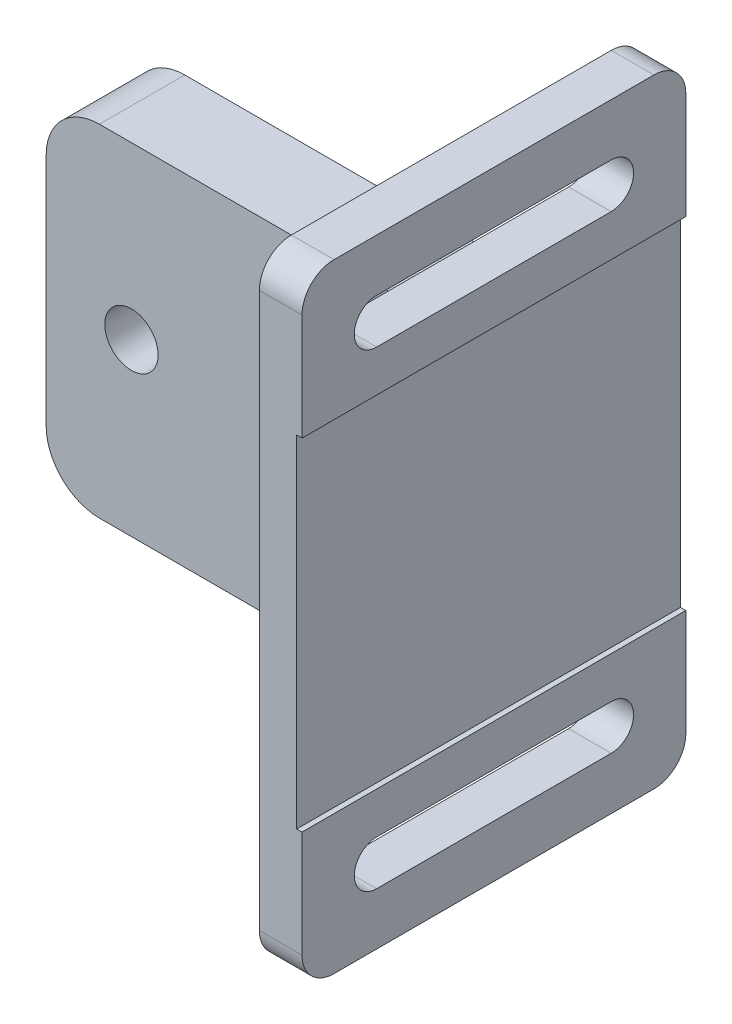
SolidWorks part; units mm, degrees
material "6061 合金"
ref_plane "前视基准面" through (0, 0, 0) normal (0, 0, 1) x (1, 0, 0)
ref_plane "上视基准面" through (0, 0, 0) normal (0, 1, 0) x (1, 0, 0)
ref_plane "右视基准面" through (0, 0, 0) normal (1, 0, 0) x (0, 0, -1)
sketch "草图1" plane through (0, 0, 0) normal (0, 0, 1) x (1, 0, 0)
  line L1 (0, 0) -> (40, 0)
  line L2 (0, 0) -> (0, 58)
  line L3 (0, 58) -> (40, 58)
  line L4 (40, 0) -> (40, 58)
  dimension "D1" = 40
  dimension "D2" = 58
extrude "凸台-拉伸2" add sketch "草图1" along normal blind 36
sketch "草图2" plane through (0, 0, 0) normal (-1, 0, 0) x (0, 0, 1)
  line L0 (36, 58) -> (36, 0) construction
  line L1 (0, 58) -> (36, 58)
  line L2 (0, 58) -> (0, 45)
  line L3 (0, 45) -> (36, 45)
  line L4 (36, 58) -> (36, 45)
  line L5 (0, 58) -> (0, 0) construction
  line L6 (36, 0) -> (0, 0)
  line L7 (36, 0) -> (36, 13)
  line L8 (36, 13) -> (0, 13)
  line L9 (0, 0) -> (0, 13)
  dimension "D1" = 13
  dimension "D2" = 13
extrude "切除-拉伸1" cut sketch "草图2" against normal offset from surface (36 mm away) 4 up to face at (40, 29, 18)
sketch "草图3" plane through (0, 0, 0) normal (-1, 0, 0) x (0, 0, 1)
  line L0 (36, 13) -> (0, 13) construction
  line L1 (36, 45) -> (20, 45)
  line L2 (36, 45) -> (36, 13)
  line L3 (36, 13) -> (20, 13)
  line L4 (20, 45) -> (20, 13)
  dimension "D1" = 16
extrude "切除-拉伸2" cut sketch "草图3" against normal up to surface (36 mm away) up to face at (36, 51.5, 18)
sketch "草图4" plane through (40, 0, 0) normal (1, 0, 0) x (0, 0, -1)
  line L0 (0, 29) -> (-40.1283, 29) construction
  line L1 (0, 0) -> (0, 58) construction
  line L2 (-29, 51) -> (-7, 51) construction
  line L3 (-29, 53.1) -> (-7, 53.1)
  line L4 (-29, 48.9) -> (-7, 48.9)
  line L5 (-29, 7) -> (-7, 7) construction
  line L6 (-29, 9.1) -> (-7, 9.1)
  line L7 (-29, 4.9) -> (-7, 4.9)
  line L8 (-18, 58) -> (-18, -2.7392) construction
  line L9 (-36, 58) -> (0, 58) construction
  arc A0 (-29, 53.1) -> (-29, 48.9) centre (-29, 51) ccw
  arc A1 (-7, 48.9) -> (-7, 53.1) centre (-7, 51) ccw
  arc A2 (-29, 9.1) -> (-29, 4.9) centre (-29, 7) ccw
  arc A3 (-7, 4.9) -> (-7, 9.1) centre (-7, 7) ccw
  point P2 (-18, 51)
  point P11 (-18, 7)
  dimension "D1" = 2.1
  dimension "D2" = 2.1
  dimension "D3" = 22
  dimension "D4" = 22
  dimension "D5" = 22
  dimension "D6" = 22
extrude "切除-拉伸3" cut sketch "草图4" against normal blind 5
hole_wizard "M6 螺纹孔1" positions "草图7" profile "草图5" tap size "M6" standard "Iso"
sketch "草图7" plane through (0, 0, 20) normal (0, 0, 1) x (1, 0, 0)
  line L0 (0, 29) -> (66.6519, 29) construction
  line L1 (0, 45) -> (0, 13) construction
  point P0 (26, 29)
  point P2 (8, 29)
  dimension "D1" = 8
  dimension "D2" = 18
sketch "草图5" plane through (26, 29, 20) normal (1, 0, 0) x (0, -1, 0)
  line L0 (0, 0) -> (0, 16.5022)
  line L1 (0, 16.5022) -> (2.5, 15)
  line L2 (2.5, 15) -> (2.5, 0)
  line L5 (2.5, 0) -> (0, 0)
  line L10 (0, 16.5022) -> (-2.5, 15) construction
  line L11 (0, -6.35) -> (0, 107.95) construction
  dimension "螺纹孔钻头直径" = 5
  dimension "螺纹孔钻头深度" = 15
  dimension "导头角度" = 118
cosmetic thread "孔螺蚊线1" parameters "D1"=8, "D2"=6
cosmetic thread "孔螺蚊线2" parameters "D1"=8, "D2"=6
sketch "草图8" plane through (0, 0, 0) normal (-1, 0, 0) x (0, 0, 1)
  line L0 (0, 13) -> (20, 13) construction
  line L1 (0, 45) -> (12, 45)
  line L2 (0, 45) -> (0, 13)
  line L3 (0, 13) -> (12, 13)
  line L4 (12, 45) -> (12, 13)
  line L5 (0, 45) -> (0, 58) construction
  dimension "D1" = 12
extrude "切除-拉伸4" cut sketch "草图8" against normal up to surface (36 mm away)
fillet "圆角1" radius 3 4 edges at (38, 0, 0) (38, 58, 0) (38, 58, 36) (38, 0, 36)
fillet "圆角2" radius 5 2 edges at (0, 13, 16) (0, 45, 16)
sketch "草图9" plane through (40, 0, 0) normal (1, 0, 0) x (0, 0, -1)
  line L0 (-36, 3) -> (-36, 55) construction
  line L1 (-36, 45) -> (0, 45)
  line L2 (-36, 45) -> (-36, 13)
  line L3 (-36, 13) -> (0, 13)
  line L4 (0, 45) -> (0, 13)
  line L5 (-33, 58) -> (-3, 58) construction
  line L6 (-33, 0) -> (-3, 0) construction
  dimension "D1" = 13
  dimension "D2" = 13
extrude "切除-拉伸5" cut sketch "草图9" against normal blind 0.5
